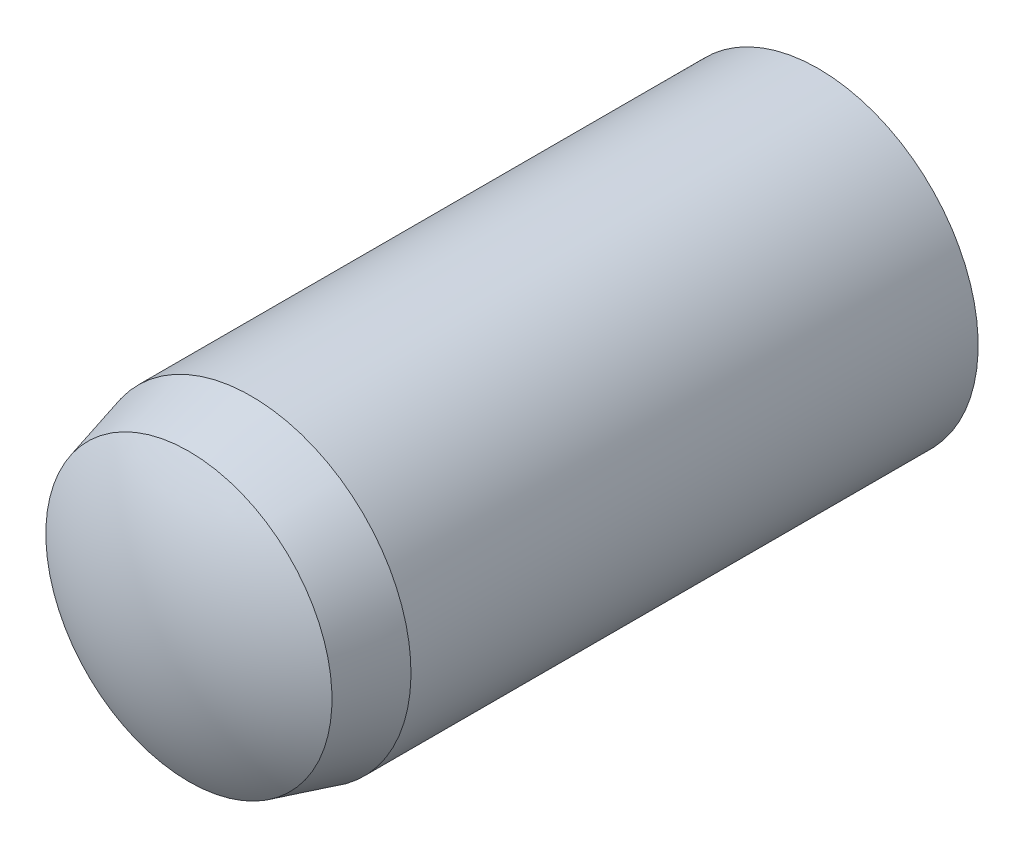
SolidWorks part; units mm, degrees
ref_plane "Front Plane" through (0, 0, 0) normal (0, 0, 1) x (1, 0, 0)
ref_plane "Top Plane" through (0, 0, 0) normal (0, 1, 0) x (1, 0, 0)
ref_plane "Right Plane" through (0, 0, 0) normal (1, 0, 0) x (0, 0, -1)
sketch "Sketch1" plane through (0, 0, 0) normal (0, 0, 1) x (1, 0, 0)
  circle A0 centre (0, 0) radius 4
  point P3 (0, 4)
  dimension "Diameter" = 8
sketch "Sketch2" plane through (0, 0, 0) normal (1, 0, 0) x (0, 0, -1)
  line L0 (-9, 0) -> (9, 0) construction
  line L1 (-9, 0) -> (-9, 4) construction
  line L2 (-9, 4) -> (9, 4)
  line L3 (9, 4) -> (9, 0) construction
  line L4 (-7.96, 3.582) -> (-6.4, 4)
  arc A0 (-9, 0) -> (-7.96, 3.582) centre (-2.3114, 0) cw
  arc A1 (9, 0) -> (7.8, 4) centre (1.7333, 0) ccw
  point P2 (0, 0)
  dimension "Length" = 18
  dimension "D1" = 15
  dimension "D2" = 1.2
  dimension "D3" = 2.6
  dimension "D4" = 1.56
sketch "Sketch3" plane through (0, 0, 0) normal (1, 0, 0) x (0, 0, -1)
  line L0 (-9, 0) -> (9, 0) construction
  line L1 (-7.96, 3.582) -> (-6.4, 4) construction
  line L2 (-9, 0) -> (9, 0)
  line L3 (-7.96, 3.582) -> (-6.4, 4)
  line L4 (-6.4, 4) -> (7.8, 4)
  arc A0 (9, 0) -> (7.8, 4) centre (1.7333, 0) ccw construction
  arc A1 (-7.96, 3.582) -> (-9, 0) centre (-2.3114, 0) ccw construction
  arc A2 (9, 0) -> (7.8, 4) centre (1.7333, 0) ccw
  arc A3 (-7.96, 3.582) -> (-9, 0) centre (-2.3114, 0) ccw
revolve "Revolve1" add sketch "Sketch3" angle 360 about L2
equation "\"D2@Sketch2\" = \"Diameter@Sketch1\" * .15"
equation "\"D3@Sketch2\" = \"Diameter@Sketch1\" * .325"
equation "\"D4@Sketch2\" = \"D3@Sketch2\" * .6"
